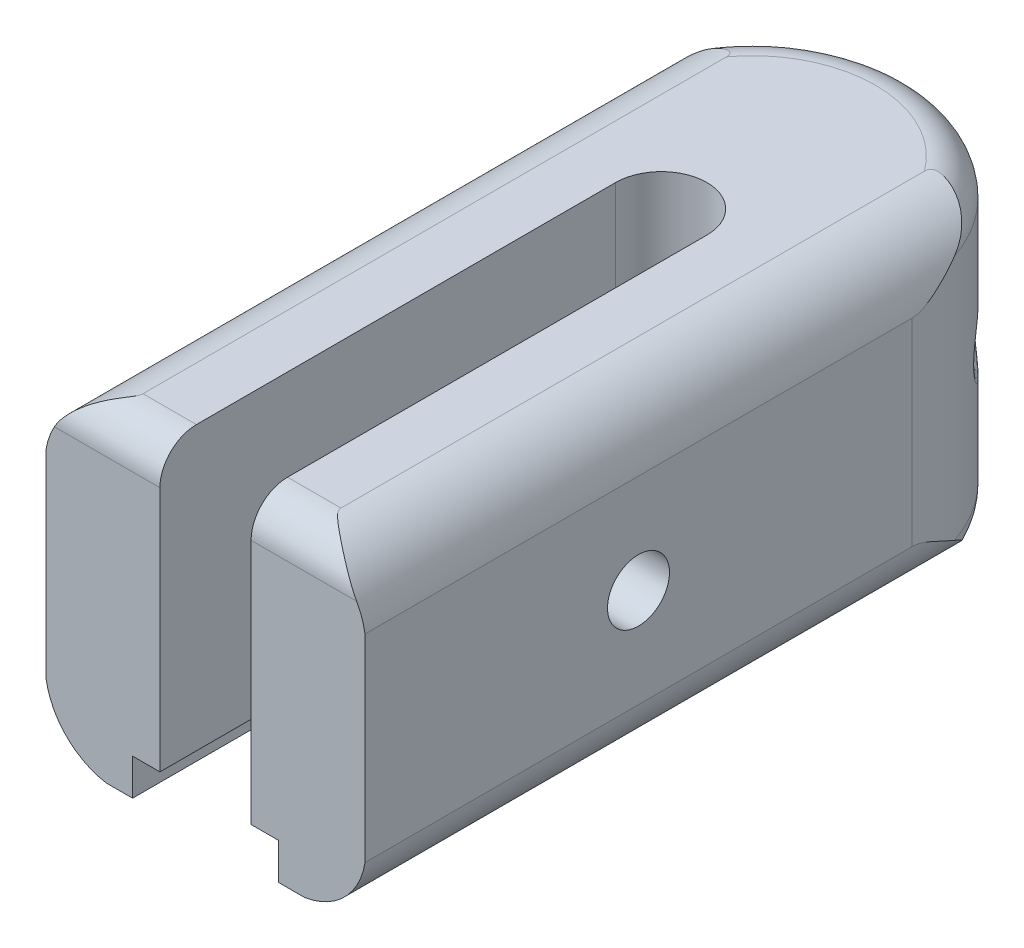
SolidWorks part; units mm, degrees
material "PET"
ref_plane "Front Plane" through (0, 0, 0) normal (0, 0, 1) x (1, 0, 0)
ref_plane "Top Plane" through (0, 0, 0) normal (0, 1, 0) x (1, 0, 0)
ref_plane "Right Plane" through (0, 0, 0) normal (1, 0, 0) x (0, 0, -1)
sketch "Sketch1" plane through (0, 0, 0) normal (0, 0, 1) x (1, 0, 0)
  line L1 (-12.7, 12.7) -> (12.7, 12.7) construction
  line L2 (-12.7, 12.7) -> (-12.7, -12.7) construction
  line L3 (-12.7, -12.7) -> (12.7, -12.7) construction
  line L4 (12.7, 12.7) -> (12.7, -12.7) construction
  line L5 (-12.7, 12.7) -> (12.7, -12.7) construction
  line L6 (-12.7, -12.7) -> (12.7, 12.7) construction
  line L7 (-11.1125, 11.1125) -> (11.1125, 11.1125)
  line L8 (-11.1125, 11.1125) -> (-11.1125, -11.1125)
  line L9 (-11.1125, -11.1125) -> (11.1125, -11.1125)
  line L10 (11.1125, 11.1125) -> (11.1125, -11.1125)
  line L11 (-11.1125, 11.1125) -> (11.1125, -11.1125) construction
  line L12 (-11.1125, -11.1125) -> (11.1125, 11.1125) construction
  point P0 (0, 0)
  point P6 (0, 0)
  dimension "D1" = 25.4
  dimension "D2" = 25.4
  dimension "D3" = 1.5875
extrude "Boss-Extrude1" add sketch "Sketch1" along normal blind 38.1
ref_plane "Plane1" through (0, 0, 0) normal (0, 1, 0) x (1, 0, 0)
sketch "Sketch3" plane through (0, 0, 0) normal (0, 1, 0) x (1, 0, 0)
  line L0 (11.1125, 0) -> (-11.1125, 0) construction
  line L1 (-11.1125, 0) -> (11.1125, 0)
  arc A0 (-11.1125, 0) -> (11.1125, 0) centre (0, 0) cw
extrude "Boss-Extrude3" add sketch "Sketch3" along normal up to surface and the other way up to surface up to face at (0, 11.1125, 19.05) other way up to face at (0, -11.1125, 19.05)
sketch "Sketch4" plane through (11.1125, 0, 0) normal (1, 0, 0) x (0, 0, -1)
  line L0 (-38.1, 0) -> (0, 0) construction
  line L1 (-38.1, -11.1125) -> (-38.1, 11.1125) construction
  line L2 (-19.05, 11.1125) -> (-19.05, -11.1125) construction
  line L3 (-38.1, 11.1125) -> (0, 11.1125) construction
  line L4 (-38.1, -11.1125) -> (0, -11.1125) construction
  line L5 (-38.1, 0) -> (0, 0) construction
  circle A0 centre (-19.05, 0) radius 2.159
  dimension "D1" = 4.318
extrude "Cut-Extrude1" cut sketch "Sketch4" against normal through all
sketch "Sketch5" plane through (0, 0, 0) normal (0, 1, 0) x (1, 0, 0)
  line L0 (0, 0) -> (-7.8577, 7.8577)
  line L1 (0, 0) -> (7.8577, 7.8577)
  line L3 (0, 24.9211) -> (0, -38.8695) construction
  arc A0 (11.1125, 0) -> (-11.1125, 0) centre (0, 0) ccw construction
  dimension "D1" = 45
  dimension "D2" = 45
ref_plane "Plane2" through (-7.8577, 0, -7.8577) normal (0.7071, 0, 0.7071) x (0.7071, 0, -0.7071)
sketch "Sketch7" plane through (-7.8577, 0, -7.8577) normal (0.7071, 0, 0.7071) x (0.7071, 0, -0.7071)
  circle A0 centre (0, 0) radius 1.5875
  dimension "D1" = 3.175
ref_plane "Plane3" through (7.8577, 0, -7.8577) normal (0.7071, 0, -0.7071) x (-0.7071, 0, -0.7071)
sketch "Sketch8" plane through (7.8577, 0, -7.8577) normal (0.7071, 0, -0.7071) x (-0.7071, 0, -0.7071)
  circle A0 centre (0, 0) radius 1.5875
  dimension "D1" = 3.175
extrude "Cut-Extrude3" cut sketch "Sketch8" against normal blind 8.89 contours A0
extrude "Cut-Extrude4" cut sketch "Sketch7" along normal blind 8.89 contours A0
sketch "Sketch10" plane through (0, -11.1125, 0) normal (0, -1, 0) x (-1, 0, 0)
  line L0 (0, -38.1) -> (0, 0) construction
  line L1 (11.1125, -38.1) -> (-11.1125, -38.1) construction
  line L2 (0, -6.35) -> (0, -44.45) construction
  line L3 (3.175, -6.35) -> (3.175, -44.45)
  line L4 (-3.175, -6.35) -> (-3.175, -44.45)
  arc A0 (3.175, -6.35) -> (-3.175, -6.35) centre (0, -6.35) ccw
  arc A1 (-3.175, -44.45) -> (3.175, -44.45) centre (0, -44.45) ccw
  point P7 (0, -25.4)
  dimension "D1" = 38.1
  dimension "D2" = 6.35
  dimension "D3" = 6.35
extrude "Cut-Extrude6" cut sketch "Sketch10" against normal through all
fillet "Fillet1" radius 0.508 2 edges at (8.8764, 0.347, -6.6856) (-6.6856, -0.347, -8.8764)
fillet "Fillet14" [suppressed] radius 0.508
sketch "Sketch14" plane through (0, 0, 0) normal (0, 1, 0) x (1, 0, 0)
  line L0 (0.3326, 2.2253) -> (-2.1037, -0.2111)
  line L1 (-2.1037, -0.2111) -> (0.0829, -2.3977)
  line L2 (0.0829, -2.3977) -> (2.5192, 0.0387)
  line L3 (2.5192, 0.0387) -> (0.3326, 2.2253)
  line L4 (0, 0) -> (-7.8577, 7.8577) construction
sketch "Sketch15" plane through (0, -11.1125, 0) normal (0, -1, 0) x (1, 0, 0)
  line L0 (-7.9375, 0) -> (7.9375, 0)
  line L4 (11.1125, 38.1) -> (3.175, 38.1)
  line L8 (11.1125, 38.1) -> (3.175, 38.1)
  line L9 (-3.175, 38.1) -> (-11.1125, 38.1)
  line L10 (-3.175, 38.1) -> (-11.1125, 38.1)
  line L11 (-3.175, 6.35) -> (-3.175, 38.1)
  line L12 (-3.175, 6.35) -> (-3.175, 38.1)
  line L13 (3.175, 38.1) -> (3.175, 6.35)
  line L14 (3.175, 38.1) -> (3.175, 6.35)
  line L18 (-11.1125, 38.1) -> (-11.1125, 0)
  line L19 (-11.1125, 38.1) -> (-11.1125, 0)
  line L20 (11.1125, 0) -> (11.1125, 38.1)
  line L21 (11.1125, 0) -> (11.1125, 38.1)
  arc A1 (-11.1125, 0) -> (11.1125, 0) centre (0, 0) ccw
  arc A2 (-11.1125, 0) -> (11.1125, 0) centre (0, 0) ccw
  arc A4 (-3.175, 6.35) -> (3.175, 6.35) centre (0, 6.35) ccw
  arc A5 (-3.175, 6.35) -> (3.175, 6.35) centre (0, 6.35) ccw
  dimension "D1" = 0
sketch "Sketch17"
extrude "Boss-Extrude15" add sketch "Sketch14" along normal mid plane 5.08
sketch "Sketch18" plane through (0, 0, 38.1) normal (0, 0, 1) x (1, 0, 0)
  line L1 (5.08, -8.5725) -> (-5.08, -8.5725)
  line L2 (5.08, -8.5725) -> (5.08, -14.6926)
  line L3 (5.08, -14.6926) -> (-5.08, -14.6926)
  line L4 (-5.08, -8.5725) -> (-5.08, -14.6926)
  line L5 (-3.175, -11.1125) -> (-11.1125, -11.1125) construction
  point P4 (0, -8.5725)
  dimension "D1" = 2.54
  dimension "D2" = 10.16
extrude "Cut-Extrude7" cut sketch "Sketch18" against normal blind 36.83
sketch "Sketch19" plane through (0, 0, 38.1) normal (0, 0, 1) x (1, 0, 0)
  line L0 (-9.6987, 9.6987) -> (9.6987, -9.6987) construction
  line L1 (-6.096, 11.176) -> (6.096, 11.176)
  line L2 (-11.176, 6.096) -> (-11.176, -6.096)
  line L3 (-6.096, -11.176) -> (6.096, -11.176)
  line L4 (11.176, 6.096) -> (11.176, -6.096)
  line L5 (-9.6987, -9.6987) -> (9.6987, 9.6987) construction
  arc A0 (-11.176, -6.096) -> (-6.096, -11.176) centre (-6.096, -6.096) ccw
  arc A1 (6.096, -11.176) -> (11.176, -6.096) centre (6.096, -6.096) ccw
  arc A2 (6.096, 11.176) -> (11.176, 6.096) centre (6.096, 6.096) cw
  arc A3 (-6.096, 11.176) -> (-11.176, 6.096) centre (-6.096, 6.096) ccw
  point P4 (11.176, 0)
  point P6 (0, 11.176)
  point P11 (0, 0)
  point P12 (0, 0)
  point P18 (11.176, -11.176)
  point P21 (11.176, 11.176)
  point P24 (-11.176, 11.176)
  dimension "D9" = 5.08
  dimension "D1" = 22.352
  dimension "D2" = 22.352
  dimension "D3" = 11.176
  dimension "D4" = 11.176
  dimension "D5" = 0
  dimension "D6" = 0
  dimension "D7" = 45
  dimension "D8" = 27.432
extrude "Cut-Extrude9" cut sketch "Sketch19" against normal through all both and the other way through all flip side to cut
fillet "Fillet15" radius 2.54 4 edges at (0, -11.1125, -11.1125) (0, 11.1125, -11.1125) (5.0359, 11.1125, 38.1) (-5.0359, 11.1125, 38.1)
equation "\"0..015in\"=0.625"
